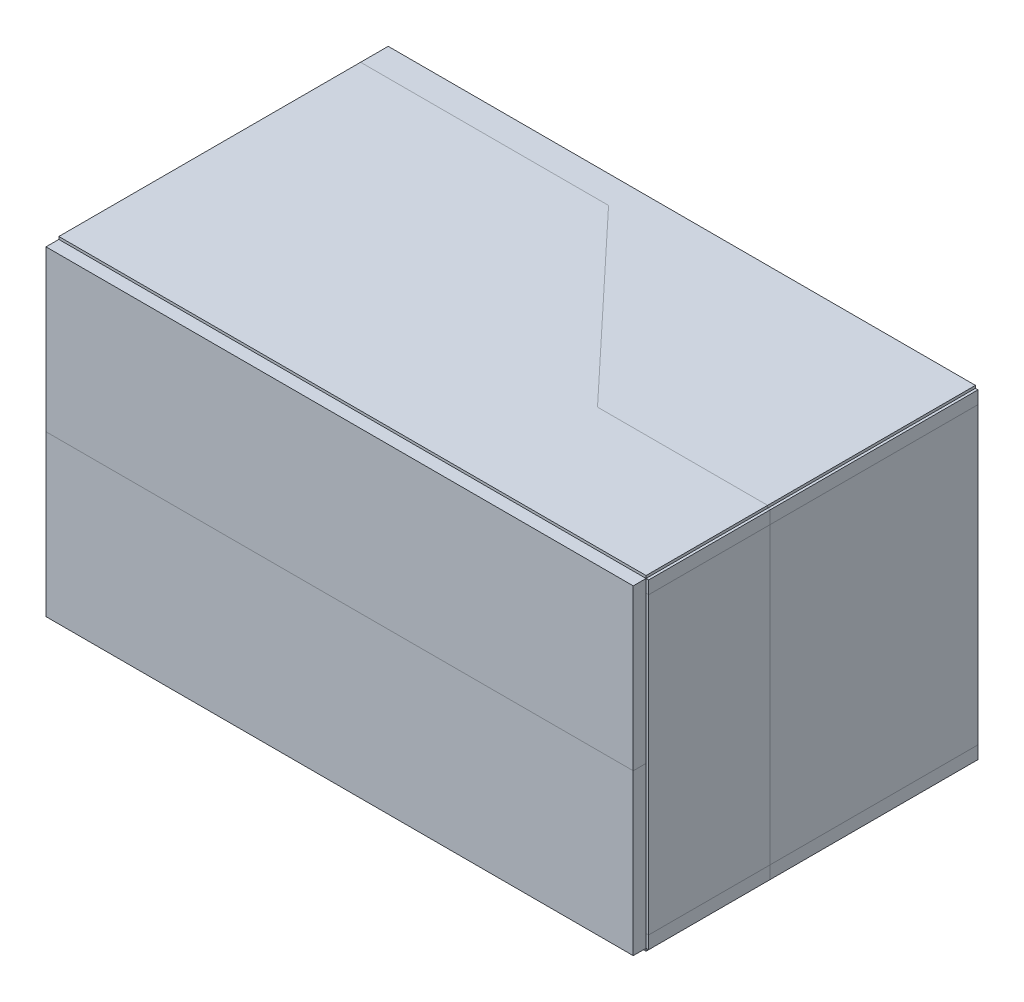
SolidWorks part; units mm, degrees
other "후면"
other "천장2"
other "천장1"
other "좌측면"
other "정면"
other "우측면"
other "바닥"
other "후면하단작음2"
other "후면상단작음2"
other "상단인테리어2"
other "하단인테리어2"
other "후면하단큼1"
other "후면상단큼1"
other "후면하단작음1"
other "후면상단작음1"
other "상단인테리어1"
other "하단인테리어1"
other "스크린"
ref_plane "정면" through (0, 0, 0) normal (0, 0, 1) x (1, 0, 0)
ref_plane "윗면" through (0, 0, 0) normal (0, 1, 0) x (1, 0, 0)
ref_plane "우측면" through (0, 0, 0) normal (1, 0, 0) x (0, 0, -1)
sketch "스케치1" plane through (0, 0, 0) normal (0, 0, 1) x (1, 0, 0)
  line L1 (51, 74.896) -> (280, 74.896)
  line L2 (51, 74.896) -> (51, -50)
  line L3 (51, -50) -> (280, -50)
  line L4 (280, 74.896) -> (280, -50)
extrude "보스-돌출1" add sketch "스케치1" along normal up to surface (7.8606 mm away)
sketch "스케치2" plane through (0, 0, 7.8606) normal (0, 0, 1) x (1, 0, 0)
  line L0 (280, 74.896) -> (280, -50) construction
  line L1 (51, 74.896) -> (280, 74.896)
  line L2 (51, 74.896) -> (51, 69.896)
  line L3 (51, 69.896) -> (280, 69.896)
  line L4 (280, 74.896) -> (280, 69.896)
  dimension "D1" = 5
extrude "컷-돌출1" cut sketch "스케치2" against normal up to surface (7.8606 mm away) contours L1 L3 L2 up to face at (165.5, 12.448, 0)
sketch "스케치4" plane through (0, 0, 7.8606) normal (0, 0, 1) x (1, 0, 0)
  line L0 (280, 69.896) -> (280, -50) construction
  line L1 (51, -50) -> (280, -50)
  line L2 (51, -50) -> (51, -45)
  line L3 (51, -45) -> (280, -45)
  line L4 (280, -50) -> (280, -45)
  line M1 (280, -50) -> (280, 69.896)
  line M3 (51, 69.896) -> (51, -50)
  line M4 (51, -50) -> (280, -50)
  dimension "D1" = 5
extrude "컷-돌출2" cut sketch "스케치4" against normal up to surface (7.8606 mm away) contours L3 M3 M4 M1 up to face at (165.5, 9.948, 0)
sketch "스케치5" plane through (0, 0, 7.8606) normal (0, 0, 1) x (1, 0, 0)
  line L0 (51, -45) -> (280, -45) construction
  line L1 (280, 69.896) -> (275, 69.896)
  line L2 (280, 69.896) -> (280, -45)
  line L3 (280, -45) -> (275, -45)
  line L4 (275, 69.896) -> (275, -45)
  line M1 (51, -45) -> (280, -45)
  line M2 (280, -45) -> (280, 69.896)
  line M3 (280, 69.896) -> (51, 69.896)
  dimension "D1" = 5
extrude "컷-돌출3" cut sketch "스케치5" against normal up to surface (7.8606 mm away) contours L4 M3 M1 M2 up to face at (165.5, 12.448, 0)
sketch "스케치6" plane through (0, 69.896, 0) normal (0, 1, 0) x (1, 0, 0)
  line L1 (51, 0) -> (280, 0)
  line L2 (51, 0) -> (51, -128.4421)
  line L3 (51, -128.4421) -> (280, -128.4421)
  line L4 (280, 0) -> (280, -128.4421)
extrude "보스-돌출3" add sketch "스케치6" along normal blind 5 separate body
sketch "스케치7" plane through (0, 0, 7.8606) normal (0, 0, 1) x (1, 0, 0)
  line L0 (51, -45) -> (275, -45) construction
  line L1 (51, 69.896) -> (56, 69.896)
  line L2 (51, 69.896) -> (51, -45)
  line L3 (51, -45) -> (56, -45)
  line L4 (56, 69.896) -> (56, -45)
  dimension "D1" = 5
extrude "보스-돌출4" add sketch "스케치7" along normal up to surface (120.5815 mm away) separate body up to face at (165.5, 72.396, 128.4421)
sketch "스케치8" plane through (0, -45, 0) normal (0, -1, 0) x (1, 0, 0)
  line L1 (51, 128.4421) -> (280, 128.4421)
  line L2 (51, 128.4421) -> (51, 0)
  line L3 (51, 0) -> (280, 0)
  line L4 (280, 128.4421) -> (280, 0)
extrude "보스-돌출5" add sketch "스케치8" along normal blind 5 separate body
sketch "스케치9" plane through (0, 0, 128.4421) normal (0, 0, 1) x (1, 0, 0)
  line L1 (51, 74.896) -> (280, 74.896)
  line L2 (51, 74.896) -> (51, 12.446)
  line L3 (51, 12.446) -> (280, 12.446)
  line L4 (280, 74.896) -> (280, 12.446)
  dimension "D1" = 62.45
extrude "보스-돌출6" add sketch "스케치9" along normal blind 5 separate body
sketch "스케치10" plane through (0, 0, 128.4421) normal (0, 0, 1) x (1, 0, 0)
  line L1 (51, 12.446) -> (280, 12.446)
  line L2 (51, 12.446) -> (51, -50)
  line L3 (51, -50) -> (280, -50)
  line L4 (280, 12.446) -> (280, -50)
extrude "보스-돌출7" add sketch "스케치10" along normal blind 5 separate body
sketch "스케치11" plane through (275, 0, 0) normal (1, 0, 0) x (0, 0, -1)
  line L1 (0, -45) -> (-128.4421, -45)
  line L2 (0, -45) -> (0, 69.896)
  line L3 (0, 69.896) -> (-128.4421, 69.896)
  line L4 (-128.4421, -45) -> (-128.4421, 69.896)
extrude "보스-돌출8" add sketch "스케치11" along normal blind 5 separate body
sketch "스케치12" plane through (0, -50, 0) normal (0, -1, 0) x (1, 0, 0)
  line L0 (51, 10.7712) -> (147.7059, 10.7712)
  line L1 (51, 128.4421) -> (51, 0) construction
  line L2 (147.7059, 10.7712) -> (213.6585, 81.0356)
  line L3 (213.6585, 81.0356) -> (280, 81.0356)
  line L4 (280, 0) -> (280, 128.4421) construction
  line L5 (51, 10.7712) -> (51, 0)
  line L6 (51, 0) -> (280, 0)
  line L7 (280, 0) -> (280, 81.0356)
extrude "보스-돌출9" add sketch "스케치12" along normal blind 1 separate body
sketch "스케치13" plane through (0, -50, 0) normal (0, -1, 0) x (1, 0, 0)
  line L0 (51, 128.4421) -> (51, 10.7712)
  line L1 (51, 10.7712) -> (147.7059, 10.7712)
  line L2 (147.7059, 10.7712) -> (213.6585, 81.0356)
  line L3 (213.6585, 81.0356) -> (280, 81.0356)
  line L4 (280, 81.0356) -> (280, 128.4421)
  line L5 (280, 128.4421) -> (51, 128.4421)
extrude "보스-돌출10" add sketch "스케치13" along normal blind 1 separate body
sketch "스케치14" plane through (280, 0, 0) normal (1, 0, 0) x (0, 0, -1)
  line L1 (-81.0356, -50) -> (-128.4421, -50)
  line L2 (-81.0356, -50) -> (-81.0356, -45)
  line L3 (-81.0356, -45) -> (-128.4421, -45)
  line L4 (-128.4421, -50) -> (-128.4421, -45)
extrude "보스-돌출11" add sketch "스케치14" along normal blind 1 separate body
sketch "스케치15" plane through (280, 0, 0) normal (1, 0, 0) x (0, 0, -1)
  line L1 (-81.0356, -50) -> (0, -50)
  line L2 (-81.0356, -50) -> (-81.0356, -45)
  line L3 (-81.0356, -45) -> (0, -45)
  line L4 (0, -50) -> (0, -45)
extrude "보스-돌출12" add sketch "스케치15" along normal blind 1 separate body
sketch "스케치16" plane through (280, 0, 0) normal (1, 0, 0) x (0, 0, -1)
  line L0 (-128.4421, 69.896) -> (0, 69.896) construction
  line L1 (-128.4421, -45) -> (-81.0356, -45)
  line L2 (-128.4421, -45) -> (-128.4421, 69.896)
  line L3 (-128.4421, 69.896) -> (-81.0356, 69.896)
  line L4 (-81.0356, -45) -> (-81.0356, 69.896)
extrude "보스-돌출13" add sketch "스케치16" along normal blind 1 separate body
sketch "스케치17" plane through (280, 0, 0) normal (1, 0, 0) x (0, 0, -1)
  line L0 (0, 74.896) -> (0, 69.896) construction
  line L1 (-81.0356, -45) -> (0, -45)
  line L2 (-81.0356, -45) -> (-81.0356, 69.896)
  line L3 (-81.0356, 69.896) -> (0, 69.896)
  line L4 (0, -45) -> (0, 69.896)
  line L5 (-128.4421, 69.896) -> (0, 69.896) construction
extrude "보스-돌출14" add sketch "스케치17" along normal blind 1 separate body
ref_plane "평면1" through (0, 12.446, 0) normal (0, 1, 0) x (1, 0, 0)
mirror "대칭 복사2" about plane through (0, 12.446, 0) normal (0, 1, 0) of bodies 112 113 114 115
other "바디 저장1"
other "바디 저장2"
sketch "스케치18" plane through (0, 0, 7.8606) normal (0, 0, 1) x (1, 0, 0)
  line L0 (76, 69.896) -> (76, 67.896)
  line L1 (51, 69.896) -> (280, 69.896) construction
  line L2 (51, -45) -> (275, -45) construction
  line L4 (76, -43) -> (76, -45)
  ellipse E0 centre (76, 12.448) end of major axis (76, 69.896) minor radius 20 (76, 69.896) -> (76, -45) ccw
  spline S1 degree 3 poles (76, 67.896) (75.5331, 67.896) (74.5994, 67.7668) (72.6093, 66.9332) (69.8748, 64.6009) (66.6087, 59.6139) (63.6639, 52.6843) (61.2158, 44.1227) (58.774, 31.0159) (57.484, 12.448) (58.774, -6.1199) (61.2158, -19.2267) (63.6639, -27.7883) (66.6087, -34.7179) (69.8748, -39.7049) (72.6093, -42.0373) (74.5994, -42.8708) (75.5331, -43) (76, -43) knots 0 0 0 0 0.098175 0.19635 0.392699 0.589049 0.785398 0.981748 1.178097 1.570796 1.963495 2.159845 2.356194 2.552544 2.748894 2.945243 3.043418 3.141593 3.141593 3.141593 3.141593
extrude "보스-돌출15" add sketch "스케치18" along normal blind 118 separate body
sketch "스케치19" plane through (0, 0, 7.8606) normal (0, 0, 1) x (1, 0, 0)
  line L0 (275, 69.896) -> (275, -45) construction
  line L1 (175, 56.9707) -> (255, 56.9707)
  line L2 (175, 56.9707) -> (175, 49.9707)
  line L3 (175, 49.9707) -> (255, 49.9707)
  line L4 (255, 56.9707) -> (255, 49.9707)
  dimension "D1" = 7
  dimension "D2" = 20
  dimension "D3" = 80
extrude "보스-돌출16" add sketch "스케치19" along normal blind 30 separate body
sketch "스케치20" plane through (255, 0, 0) normal (1, 0, 0) x (0, 0, -1)
  line L0 (-37.8606, 49.9707) -> (-37.8606, 56.9707)
  line L1 (-37.8606, 49.9707) -> (-80.1209, 60.896)
  line L2 (-37.8606, 56.9707) -> (-80.1209, 67.896)
  line L3 (-80.1209, 60.896) -> (-80.1209, 67.896)
  line L4 (-37.8606, 49.9707) -> (-37.8606, 56.9707) construction
  line L5 (-37.8606, 49.9707) -> (-7.8606, 49.9707) construction
  line L6 (-125.8606, 67.896) -> (-7.8606, 67.896) construction
extrude "보스-돌출17" add sketch "스케치20" against normal up to surface (80 mm away) up to face at (175, 53.4707, 22.8606)
sketch "스케치21" plane through (0, 37.6655, -9.7374) normal (0, -0.9682, 0.2503) x (1, 0, 0)
  line L0 (253, 90.8125) -> (177, 90.8125)
  line L1 (177, 90.8125) -> (177, 51.1629)
  line L2 (177, 51.1629) -> (253, 51.1629)
  line L3 (253, 51.1629) -> (253, 90.8125)
  line L4 (175, 92.8125) -> (175, 49.1629)
  line L5 (175, 49.1629) -> (255, 49.1629)
  line L6 (255, 49.1629) -> (255, 92.8125)
  line L7 (255, 92.8125) -> (175, 92.8125)
  line L8 (175, 92.8125) -> (175, 49.1629)
  line L9 (175, 49.1629) -> (255, 49.1629)
  line L10 (255, 49.1629) -> (255, 92.8125)
  line L11 (255, 92.8125) -> (175, 92.8125)
  dimension "D1" = 0
  dimension "D2" = 2
extrude "컷-돌출4" cut sketch "스케치21" against normal blind 5 contours L2 L3 L0 L1
sketch "스케치22" plane through (0, 0, 7.8606) normal (0, 0, 1) x (1, 0, 0)
  line L1 (80.4677, 62.5927) -> (166.297, 62.5927)
  line L2 (80.4677, 62.5927) -> (80.4677, 51.9011)
  line L3 (80.4677, 51.9011) -> (166.297, 51.9011)
  line L4 (166.297, 62.5927) -> (166.297, 51.9011)
extrude "보스-돌출18" add sketch "스케치22" along normal blind 50 separate body
sketch "스케치23" plane through (0, 0, 57.8606) normal (0, 0, 1) x (1, 0, 0)
  line L0 (166.297, 62.5927) -> (80.4677, 62.5927) construction
  line L1 (85.4677, 62.5927) -> (161.297, 62.5927)
  line L2 (85.4677, 62.5927) -> (85.4677, 51.9011)
  line L3 (85.4677, 51.9011) -> (161.297, 51.9011)
  line L4 (161.297, 62.5927) -> (161.297, 51.9011)
  line L5 (80.4677, 51.9011) -> (166.297, 51.9011) construction
  line L6 (80.4677, 62.5927) -> (80.4677, 51.9011) construction
  line L7 (166.297, 51.9011) -> (166.297, 62.5927) construction
  dimension "D1" = 5
  dimension "D2" = 5
extrude "컷-돌출5" cut sketch "스케치23" against normal blind 45
sketch "스케치24" plane through (85.4677, 0, 0) normal (1, 0, 0) x (0, 0, -1)
  line L0 (-12.8606, 62.5927) -> (-57.8606, 62.5927) construction
  line L1 (-45.5028, 62.5927) -> (-43.5028, 62.5927)
  line L2 (-45.5028, 62.5927) -> (-45.5028, 51.9011)
  line L3 (-45.5028, 51.9011) -> (-43.5028, 51.9011)
  line L4 (-43.5028, 62.5927) -> (-43.5028, 51.9011)
  line L5 (-12.8606, 51.9011) -> (-57.8606, 51.9011) construction
  dimension "D1" = 2
extrude "보스-돌출19" add sketch "스케치24" along normal up to surface (75.8293 mm away) up to face at (161.297, 57.2469, 35.3606)
sketch "스케치25" plane through (0, 0, 45.5028) normal (0, 0, 1) x (1, 0, 0)
  circle A0 centre (95.092, 57.2523) radius 3.5
  circle A1 centre (110.092, 57.2523) radius 3.5
  circle A2 centre (125.092, 57.2523) radius 3.5
  circle A3 centre (140.092, 57.2523) radius 3.5
  circle A4 centre (155.092, 57.2523) radius 3.5
  dimension "D1" = 7
  dimension "D2" = 5
extrude "컷-돌출6" cut sketch "스케치25" against normal blind 5
sketch "스케치26" plane through (0, 0, 12.8606) normal (0, 0, 1) x (1, 0, 0)
  line L1 (94.8011, 53.7644) -> (95.6011, 53.7644)
  line L2 (94.8011, 53.7644) -> (94.8011, 54.2644)
  line L3 (94.8011, 54.2644) -> (95.6011, 54.2644)
  line L4 (95.6011, 53.7644) -> (95.6011, 54.2644)
  circle A0 centre (95.092, 57.2523) radius 3.5 construction
  dimension "D1" = 0.5
  dimension "D2" = 0.8
extrude "보스-돌출20" add sketch "스케치26" along normal blind 51 separate body
sketch "스케치27" plane through (95.6011, 0, 0) normal (1, 0, 0) x (0, 0, -1)
  line L1 (-63.8606, 53.7644) -> (-67.9598, 53.7644)
  line L2 (-63.8606, 53.7644) -> (-63.8606, 60.8969)
  line L3 (-63.8606, 60.8969) -> (-67.9598, 60.8969)
  line L4 (-67.9598, 53.7644) -> (-67.9598, 60.8969)
extrude "보스-돌출21" add sketch "스케치27" against normal blind 0.8
fillet "필렛1" radius 1 1 edges at (95.2011, 60.8969, 67.9598)
fillet "필렛2" radius 1 1 edges at (95.2011, 60.8969, 63.8606)
sketch "스케치28" plane through (95.6011, 0, 0) normal (1, 0, 0) x (0, 0, -1)
  line L0 (-66.8605, 54.8776) -> (-66.8605, 59.0401) construction
  line L1 (-67.1597, 54.8776) -> (-67.1597, 59.0401)
  line L2 (-66.5613, 54.8776) -> (-66.5613, 59.0401)
  line L3 (-65.8605, 54.8776) -> (-65.8605, 59.0401) construction
  line L4 (-66.1597, 54.8776) -> (-66.1597, 59.0401)
  line L5 (-65.5613, 54.8776) -> (-65.5613, 59.0401)
  line L6 (-64.8605, 54.8776) -> (-64.8605, 59.0401) construction
  line L7 (-65.1597, 54.8776) -> (-65.1597, 59.0401)
  line L8 (-64.5613, 54.8776) -> (-64.5613, 59.0401)
  arc A0 (-67.1597, 54.8776) -> (-66.5613, 54.8776) centre (-66.8605, 54.8776) ccw
  arc A1 (-66.5613, 59.0401) -> (-67.1597, 59.0401) centre (-66.8605, 59.0401) ccw
  arc A2 (-66.1597, 54.8776) -> (-65.5613, 54.8776) centre (-65.8605, 54.8776) ccw
  arc A3 (-65.5613, 59.0401) -> (-66.1597, 59.0401) centre (-65.8605, 59.0401) ccw
  arc A4 (-65.1597, 54.8776) -> (-64.5613, 54.8776) centre (-64.8605, 54.8776) ccw
  arc A5 (-64.5613, 59.0401) -> (-65.1597, 59.0401) centre (-64.8605, 59.0401) ccw
  point P2 (-66.8605, 56.9589)
  point P11 (-65.8605, 56.9589)
  point P18 (-64.8605, 56.9589)
  dimension "D1" = 0.5984
  dimension "D2" = 4.1626
  dimension "D3" = 3
extrude "컷-돌출7" cut sketch "스케치28" against normal blind 0.2 draft 30
pattern_linear "선형 패턴1" count 5 spacing 15 along (1, 0, 0) of bodies 168
sketch "스케치29" plane through (0, 0, 7.8606) normal (0, 0, 1) x (1, 0, 0)
  line L0 (275, 69.896) -> (275, -45) construction
  line L1 (95, 30.3782) -> (195, 30.3782)
  line L2 (95, 30.3782) -> (95, -29.6218)
  line L3 (95, -29.6218) -> (195, -29.6218)
  line L4 (195, 30.3782) -> (195, -29.6218)
  dimension "D1" = 100
  dimension "D2" = 60
  dimension "D3" = 80
extrude "보스-돌출22" add sketch "스케치29" along normal blind 1 separate body
sketch "스케치34" plane through (0, 0, 8.8606) normal (0, 0, 1) x (1, 0, 0)
  line L0 (195, -29.6218) -> (195, 30.3782) construction
  line L1 (195, 30.3782) -> (95, 30.3782) construction
  circle A0 centre (175, 15.3782) radius 1.5
  dimension "D1" = 3
  dimension "D2" = 20
  dimension "D3" = 15
extrude "보스-돌출24" add sketch "스케치34" along normal blind 5 separate body
sketch "스케치35" plane through (0, 0, 13.8606) normal (0, 0, 1) x (1, 0, 0)
  circle A0 centre (175, 15.3782) radius 1.3
  circle A1 centre (175, 15.3782) radius 1.5
  circle A2 centre (175, 15.3782) radius 1.5
  dimension "D1" = 0
  dimension "D2" = 0.2
extrude "컷-돌출9" cut sketch "스케치35" against normal blind 5 draft 10 contours A0
ref_plane "평면3" through (0, 0, 15.8606) normal (0, 0, 1) x (1, 0, 0)
sketch "스케치37" plane through (0, 0, 15.8606) normal (0, 0, 1) x (1, 0, 0)
  line L0 (175, 16.8782) -> (175, 13.8782)
  arc A0 (175, 13.8782) -> (175, 16.8782) centre (175, 15.3782) ccw
revolve "회전2" add sketch "스케치37" angle 360 about L0
sketch "스케치38" plane through (0, 0, 7.8606) normal (0, 0, 1) x (1, 0, 0)
  line L1 (235.5304, 7.1458) -> (245.5304, 7.1458)
  line L2 (235.5304, 7.1458) -> (235.5304, -2.8542)
  line L3 (235.5304, -2.8542) -> (245.5304, -2.8542)
  line L4 (245.5304, 7.1458) -> (245.5304, -2.8542)
  dimension "D1" = 10
  dimension "D2" = 10
extrude "보스-돌출25" add sketch "스케치38" along normal blind 27 separate body
sketch "스케치39" plane through (0, 0, 34.8606) normal (0, 0, 1) x (1, 0, 0)
  line L0 (235.5304, 2.1458) -> (245.5304, 2.1458) construction
  line L1 (218.0304, 24.6458) -> (263.0304, 24.6458)
  line L2 (218.0304, 24.6458) -> (218.0304, -20.3542)
  line L3 (218.0304, -20.3542) -> (263.0304, -20.3542)
  line L4 (263.0304, 24.6458) -> (263.0304, -20.3542)
  line L5 (218.0304, 24.6458) -> (263.0304, -20.3542) construction
  line L6 (218.0304, -20.3542) -> (263.0304, 24.6458) construction
  line L7 (235.5304, 7.1458) -> (235.5304, -2.8542) construction
  line L8 (245.5304, -2.8542) -> (245.5304, 7.1458) construction
  point P0 (240.5304, 2.1458)
  point P11 (240.5304, 2.1458)
  dimension "D1" = 45
  dimension "D2" = 45
extrude "보스-돌출26" add sketch "스케치39" along normal blind 5
sketch "스케치41" plane through (0, 69.896, 0) normal (0, -1, 0) x (1, 0, 0)
  line L0 (147.7755, 128.4421) -> (280, 128.4421)
  line L1 (147.7755, 128.4421) -> (212.6752, 7.8606)
  line L3 (212.6752, 7.8606) -> (213.8109, 7.8606)
  line L4 (51, 128.4421) -> (280, 128.4421) construction
  line L5 (175, 7.8606) -> (255, 7.8606) construction
  line L6 (280, 81.0356) -> (280, 128.4421) construction
  line L7 (280, 128.4421) -> (280, 0) construction
  line L8 (213.8109, 7.8606) -> (280, 7.8606)
  line L9 (280, 7.8606) -> (280, 128.4421)
extrude "컷-돌출10" cut sketch "스케치41" against normal blind 0.1
